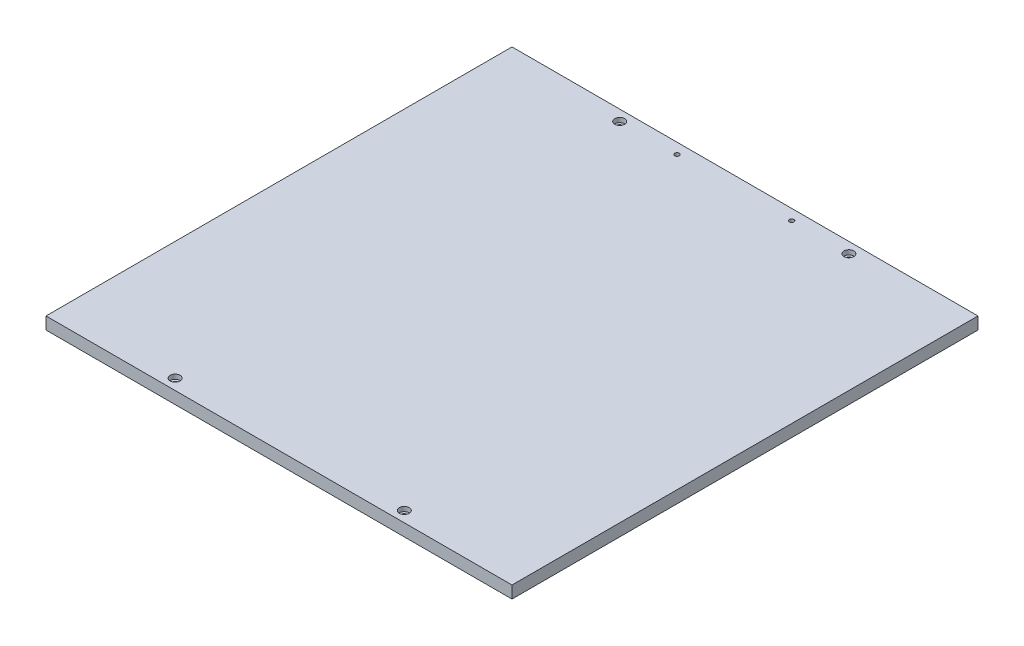
SolidWorks part; units mm, degrees
ref_plane "前视基准面" through (0, 0, 0) normal (0, 0, 1) x (1, 0, 0)
ref_plane "上视基准面" through (0, 0, 0) normal (0, 1, 0) x (1, 0, 0)
ref_plane "右视基准面" through (0, 0, 0) normal (1, 0, 0) x (0, 0, -1)
sketch "草图1" plane through (0, 0, 0) normal (0, 1, 0) x (1, 0, 0)
  line L1 (-152.5, -152.5) -> (152.5, -152.5)
  line L2 (-152.5, -152.5) -> (-152.5, 152.5)
  line L3 (-152.5, 152.5) -> (152.5, 152.5)
  line L4 (152.5, -152.5) -> (152.5, 152.5)
  line L5 (-152.5, -152.5) -> (152.5, 152.5) construction
  line L6 (-152.5, 152.5) -> (152.5, -152.5) construction
  point P0 (0, 0)
  dimension "D1" = 305
  dimension "D2" = 305
extrude "凸台-拉伸1" add sketch "草图1" along normal blind 8
sketch "草图2" plane through (0, 8, 0) normal (0, 1, 0) x (1, 0, 0)
  line L0 (152.5, -152.5) -> (152.5, 152.5) construction
  line L1 (-152.5, -152.5) -> (152.5, -152.5) construction
  point P0 (-75, 145.5)
  point P1 (75, 145.5)
  point P2 (75, -145.5)
  point P3 (-75, -145.5)
  point P4 (-37.5, 145.5)
  point P5 (37.5, 145.5)
  dimension "D1" = 77.5
  dimension "D2" = 115
  dimension "D3" = 75
  dimension "D4" = 150
  dimension "D5" = 150
  dimension "D6" = 77.5
  dimension "D7" = 291
  dimension "D8" = 7
hole_wizard "M1.6 六角头螺栓的柱形沉头孔1" positions "草图4" profile "草图5" counterbore size "M1.6" standard "GB" end condition through all
sketch "草图4" plane through (0, 8, 0) normal (0, 1, 0) x (1, 0, 0)
  point P0 (-75, 145.5)
  point P3 (75, 145.5)
  point P6 (75, -145.5)
  point P9 (-75, -145.5)
sketch "草图5" plane through (-75, 8, -145.5) normal (1, 0, 0) x (0, 0, 1)
  line L0 (0, 0) -> (0, 8)
  line L1 (0, 8) -> (1.7, 8)
  line L3 (1.7, 8) -> (1.7, 3)
  line L4 (1.7, 3) -> (3.25, 3)
  line L5 (3.25, 3) -> (3.25, 0)
  line L7 (3.25, 0) -> (0, 0)
  line L11 (0, -6.35) -> (0, 107.95) construction
  dimension "通孔孔直径" = 3.4
  dimension "通孔孔深度" = 8
  dimension "柱形沉头孔直径" = 6.5
  dimension "柱形沉头孔深度" = 3
hole_wizard "M3 螺纹孔1" positions "3D草图2" profile "草图6" tap size "M3" standard "GB" end condition through all
sketch3d "3D草图2"
  point P0 (-37.5, 8, -145.5)
  point P3 (37.5, 8, -145.5)
cosmetic thread "孔螺蚊线1" parameters "D2"=3
cosmetic thread "孔螺蚊线2" parameters "D2"=3
sketch "草图6" plane through (-37.5, 8, -145.5) normal (1, 0, 0) x (0, 0, 1)
  line L0 (0, 0) -> (0, 8)
  line L1 (0, 8) -> (1.5, 8)
  line L2 (1.5, 8) -> (1.5, 0)
  line L5 (1.5, 0) -> (0, 0)
  line L11 (0, -6.35) -> (0, 107.95) construction
  dimension "通孔螺纹孔钻头直径" = 3
  dimension "通孔螺纹孔钻头深度" = 8
